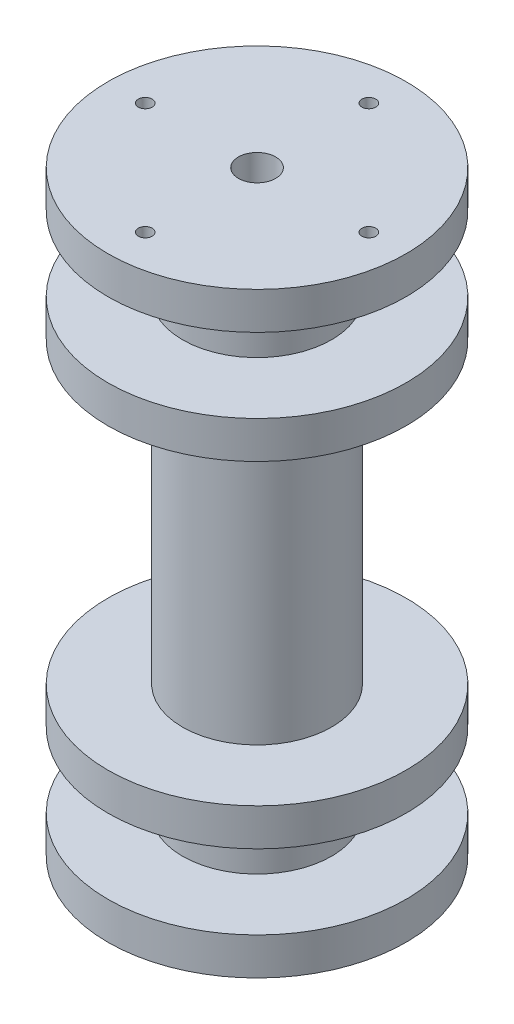
SolidWorks part; units mm, degrees
ref_plane "Front Plane" through (0, 0, 0) normal (0, 0, 1) x (1, 0, 0)
ref_plane "Top Plane" through (0, 0, 0) normal (0, 1, 0) x (1, 0, 0)
ref_plane "Right Plane" through (0, 0, 0) normal (1, 0, 0) x (0, 0, -1)
sketch "Sketch1" plane through (0, 0, 0) normal (0, 1, 0) x (1, 0, 0)
  line L0 (-25.4, 0) -> (25.4, 0) construction
  circle A0 centre (0, 0) radius 25.4
  dimension "D1" = 50.8
extrude "Boss-Extrude1" add sketch "Sketch1" along normal blind 101.6
sketch "Sketch2" plane through (0, 0, 0) normal (1, 0, 0) x (0, 0, -1)
  line L0 (25.4, 0) -> (25.4, 101.6) construction
  line L1 (25.4, 95.25) -> (12.7, 95.25)
  line L2 (25.4, 95.25) -> (25.4, 82.55)
  line L3 (25.4, 82.55) -> (12.7, 82.55)
  line L4 (12.7, 95.25) -> (12.7, 82.55)
  line L5 (25.4, 0) -> (25.4, 101.6) construction
  line L6 (25.4, 19.05) -> (12.7, 19.05)
  line L7 (25.4, 19.05) -> (25.4, 6.35)
  line L8 (25.4, 6.35) -> (12.7, 6.35)
  line L9 (12.7, 19.05) -> (12.7, 6.35)
  line L10 (25.4, 0) -> (-25.4, 0) construction
  line L11 (25.4, 101.6) -> (-25.4, 101.6) construction
  line L12 (25.4, 0) -> (25.4, 101.6) construction
  line L13 (25.4, 76.2) -> (12.7, 76.2)
  line L14 (25.4, 76.2) -> (25.4, 25.4)
  line L15 (25.4, 25.4) -> (12.7, 25.4)
  line L16 (12.7, 76.2) -> (12.7, 25.4)
  dimension "D1" = 12.7
  dimension "D2" = 6.35
  dimension "D3" = 6.35
  dimension "D4" = 12.7
  dimension "D5" = 6.35
  dimension "D6" = 6.35
ref_axis "Axis1" [suppressed] through (0, 101.6, 0) along (0, -1, 0)
revolve "Cut-Revolve1" cut sketch "Sketch2" angle 360 about axis through (0, 101.6, 0) along (0, -1, 0)
sketch "Sketch3" plane through (0, 101.6, 0) normal (0, 1, 0) x (1, 0, 0)
  circle A0 centre (0, 0) radius 3.175
  dimension "D1" = 6.35
extrude "Cut-Extrude1" cut sketch "Sketch3" against normal up to next
sketch "Sketch4" plane through (0, 101.6, 0) normal (0, 1, 0) x (1, 0, 0)
  circle A0 centre (0, 0) radius 19.05 construction
  circle A1 centre (-19.05, 0) radius 1.1874
  circle A2 centre (0, 19.05) radius 1.1874
  circle A3 centre (19.05, 0) radius 1.1874
  circle A4 centre (0, -19.05) radius 1.1874
  point P13 (0, 0)
  dimension "D1" = 38.1
  dimension "D2" = 2.3749
  dimension "D3" = 4
extrude "Cut-Extrude2" cut sketch "Sketch4" against normal up to next
